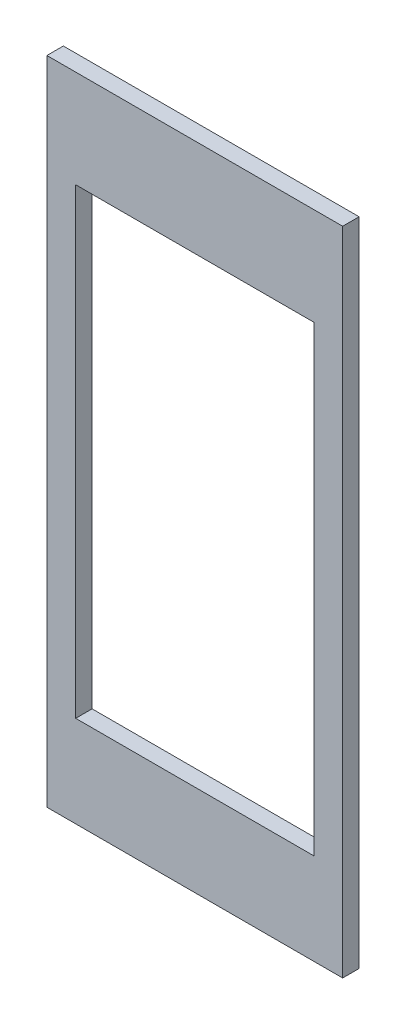
SolidWorks part; units mm, degrees
ref_plane "Front Plane" through (0, 0, 0) normal (0, 0, 1) x (1, 0, 0)
ref_plane "Top Plane" through (0, 0, 0) normal (0, 1, 0) x (1, 0, 0)
ref_plane "Right Plane" through (0, 0, 0) normal (1, 0, 0) x (0, 0, -1)
sketch "Sketch1" plane through (0, 0, 0) normal (0, 0, 1) x (1, 0, 0)
  line L1 (-28.575, 62.9047) -> (28.575, 62.9047)
  line L2 (-28.575, 62.9047) -> (-28.575, -62.9047)
  line L3 (-28.575, -62.9047) -> (28.575, -62.9047)
  line L4 (28.575, 62.9047) -> (28.575, -62.9047)
  line L5 (-23.0188, 44.0531) -> (23.0188, 44.0531)
  line L6 (-23.0188, 44.0531) -> (-23.0188, -45.2437)
  line L7 (-23.0188, -45.2437) -> (23.0188, -45.2437)
  line L8 (23.0188, 44.0531) -> (23.0188, -45.2437)
  point P5 (0, 62.9047)
  point P6 (-28.575, 0)
  point P14 (0, 44.0531)
  point P15 (0, -45.2437)
  point P16 (-21.3811, 37.2865)
  dimension "D1" = 125.8094
  dimension "D2" = 57.15
  dimension "D3" = 5.5563
  dimension "D4" = 89.2969
  dimension "D5" = 45.2437
extrude "Boss-Extrude1" add sketch "Sketch1" along normal mid plane 3.175
